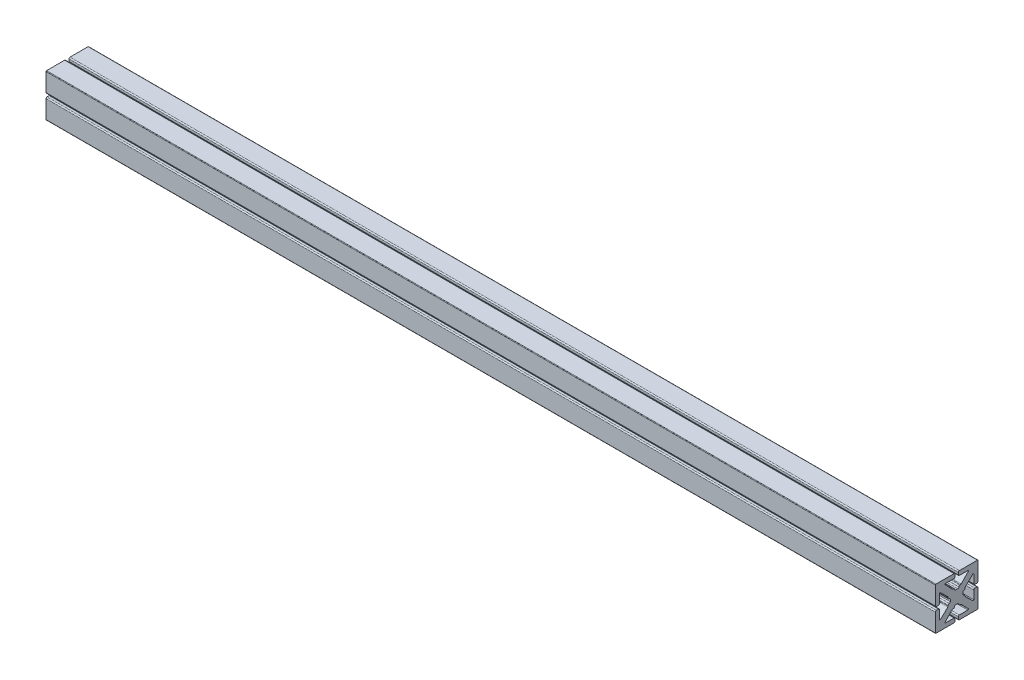
SolidWorks part; units mm, degrees
material "1060 Alloy"
ref_plane "Front Plane" through (0, 0, 0) normal (0, 0, 1) x (1, 0, 0)
ref_plane "Top Plane" through (0, 0, 0) normal (0, 1, 0) x (1, 0, 0)
ref_plane "Right Plane" through (0, 0, 0) normal (1, 0, 0) x (0, 0, -1)
sketch "Sketch1" plane through (0, 0, 0) normal (1, 0, 0) x (0, 0, -1)
  line L0 (0, 0) -> (0, 1.4986) construction
  line L1 (-0.2413, 1.4986) -> (0.2413, 1.4986)
  line L2 (5.0038, 0.635) -> (5.0038, 4.8768)
  line L3 (0.7493, 2.0066) -> (0.8825, 2.0066)
  line L4 (1.0655, 2.0845) -> (2.7141, 3.7982)
  line L5 (2.6226, 4.0132) -> (0.635, 4.0132)
  line L6 (0.381, 4.2672) -> (0.381, 4.7498)
  line L7 (0.635, 5.0038) -> (4.8768, 5.0038)
  line L8 (5.0038, 5.0038) -> (0, 0) construction
  line L9 (0, 0) -> (8.6271, 0) construction
  line L10 (0, 0) -> (0, 5.0038) construction
  line L11 (4.2672, 0.381) -> (4.7498, 0.381)
  line L12 (4.0132, 2.6226) -> (4.0132, 0.635)
  line L13 (2.0845, 1.0655) -> (3.7982, 2.7141)
  line L14 (2.0066, 0.7493) -> (2.0066, 0.8825)
  line L15 (1.4986, -0.2413) -> (1.4986, 0.2413)
  line L16 (0, 0) -> (1.4986, 0) construction
  line L17 (-0.2413, -1.4986) -> (0.2413, -1.4986)
  line L18 (0.7493, -2.0066) -> (0.8825, -2.0066)
  line L19 (1.0655, -2.0845) -> (2.7141, -3.7982)
  line L20 (2.6226, -4.0132) -> (0.635, -4.0132)
  line L21 (0.381, -4.2672) -> (0.381, -4.7498)
  line L22 (0.635, -5.0038) -> (4.8768, -5.0038)
  line L23 (5.0038, -0.635) -> (5.0038, -4.8768)
  line L24 (4.2672, -0.381) -> (4.7498, -0.381)
  line L25 (4.0132, -2.6226) -> (4.0132, -0.635)
  line L26 (2.0845, -1.0655) -> (3.7982, -2.7141)
  line L27 (2.0066, -0.7493) -> (2.0066, -0.8825)
  line L28 (-0.7493, 2.0066) -> (-0.8825, 2.0066)
  line L29 (-1.0655, 2.0845) -> (-2.7141, 3.7982)
  line L30 (-2.6226, 4.0132) -> (-0.635, 4.0132)
  line L31 (-0.381, 4.2672) -> (-0.381, 4.7498)
  line L32 (-0.635, 5.0038) -> (-4.8768, 5.0038)
  line L33 (-5.0038, 0.635) -> (-5.0038, 4.8768)
  line L34 (-4.2672, 0.381) -> (-4.7498, 0.381)
  line L35 (-4.0132, 2.6226) -> (-4.0132, 0.635)
  line L36 (-2.0845, 1.0655) -> (-3.7982, 2.7141)
  line L37 (-2.0066, 0.7493) -> (-2.0066, 0.8825)
  line L38 (-1.4986, -0.2413) -> (-1.4986, 0.2413)
  line L39 (-2.0066, -0.7493) -> (-2.0066, -0.8825)
  line L40 (-2.0845, -1.0655) -> (-3.7982, -2.7141)
  line L41 (-4.0132, -2.6226) -> (-4.0132, -0.635)
  line L42 (-4.2672, -0.381) -> (-4.7498, -0.381)
  line L43 (-5.0038, -0.635) -> (-5.0038, -4.8768)
  line L44 (-0.635, -5.0038) -> (-4.8768, -5.0038)
  line L45 (-0.381, -4.2672) -> (-0.381, -4.7498)
  line L46 (-2.6226, -4.0132) -> (-0.635, -4.0132)
  line L47 (-1.0655, -2.0845) -> (-2.7141, -3.7982)
  line L48 (-0.7493, -2.0066) -> (-0.8825, -2.0066)
  arc A0 (2.7141, 3.7982) -> (2.6226, 4.0132) centre (2.6226, 3.8862) ccw
  arc A1 (0.4953, 1.7526) -> (0.7493, 2.0066) centre (0.7493, 1.7526) cw
  arc A2 (0.8825, 2.0066) -> (1.0655, 2.0845) centre (0.8825, 2.2606) ccw
  arc A3 (0.635, 4.0132) -> (0.381, 4.2672) centre (0.635, 4.2672) cw
  arc A4 (0.381, 4.7498) -> (0.635, 5.0038) centre (0.635, 4.7498) cw
  arc A5 (0.2413, 1.4986) -> (0.4953, 1.7526) centre (0.2413, 1.7526) ccw
  arc A6 (4.7498, 0.381) -> (5.0038, 0.635) centre (4.7498, 0.635) ccw
  arc A7 (4.0132, 0.635) -> (4.2672, 0.381) centre (4.2672, 0.635) ccw
  arc A8 (3.7982, 2.7141) -> (4.0132, 2.6226) centre (3.8862, 2.6226) cw
  arc A9 (2.0066, 0.8825) -> (2.0845, 1.0655) centre (2.2606, 0.8825) cw
  arc A10 (1.7526, 0.4953) -> (2.0066, 0.7493) centre (1.7526, 0.7493) ccw
  arc A11 (1.4986, 0.2413) -> (1.7526, 0.4953) centre (1.7526, 0.2413) cw
  arc A12 (0.2413, -1.4986) -> (0.4953, -1.7526) centre (0.2413, -1.7526) cw
  arc A13 (0.4953, -1.7526) -> (0.7493, -2.0066) centre (0.7493, -1.7526) ccw
  arc A14 (0.8825, -2.0066) -> (1.0655, -2.0845) centre (0.8825, -2.2606) cw
  arc A15 (2.7141, -3.7982) -> (2.6226, -4.0132) centre (2.6226, -3.8862) cw
  arc A16 (0.635, -4.0132) -> (0.381, -4.2672) centre (0.635, -4.2672) ccw
  arc A17 (0.381, -4.7498) -> (0.635, -5.0038) centre (0.635, -4.7498) ccw
  arc A18 (4.7498, -0.381) -> (5.0038, -0.635) centre (4.7498, -0.635) cw
  arc A19 (4.0132, -0.635) -> (4.2672, -0.381) centre (4.2672, -0.635) cw
  arc A20 (3.7982, -2.7141) -> (4.0132, -2.6226) centre (3.8862, -2.6226) ccw
  arc A21 (2.0066, -0.8825) -> (2.0845, -1.0655) centre (2.2606, -0.8825) ccw
  arc A22 (1.7526, -0.4953) -> (2.0066, -0.7493) centre (1.7526, -0.7493) cw
  arc A23 (1.4986, -0.2413) -> (1.7526, -0.4953) centre (1.7526, -0.2413) ccw
  arc A24 (-0.2413, 1.4986) -> (-0.4953, 1.7526) centre (-0.2413, 1.7526) cw
  arc A25 (-0.4953, 1.7526) -> (-0.7493, 2.0066) centre (-0.7493, 1.7526) ccw
  arc A26 (-0.8825, 2.0066) -> (-1.0655, 2.0845) centre (-0.8825, 2.2606) cw
  arc A27 (-2.7141, 3.7982) -> (-2.6226, 4.0132) centre (-2.6226, 3.8862) cw
  arc A28 (-0.635, 4.0132) -> (-0.381, 4.2672) centre (-0.635, 4.2672) ccw
  arc A29 (-0.381, 4.7498) -> (-0.635, 5.0038) centre (-0.635, 4.7498) ccw
  arc A30 (-4.7498, 0.381) -> (-5.0038, 0.635) centre (-4.7498, 0.635) cw
  arc A31 (-4.0132, 0.635) -> (-4.2672, 0.381) centre (-4.2672, 0.635) cw
  arc A32 (-3.7982, 2.7141) -> (-4.0132, 2.6226) centre (-3.8862, 2.6226) ccw
  arc A33 (-2.0066, 0.8825) -> (-2.0845, 1.0655) centre (-2.2606, 0.8825) ccw
  arc A34 (-1.7526, 0.4953) -> (-2.0066, 0.7493) centre (-1.7526, 0.7493) cw
  arc A35 (-1.4986, 0.2413) -> (-1.7526, 0.4953) centre (-1.7526, 0.2413) ccw
  arc A36 (-1.4986, -0.2413) -> (-1.7526, -0.4953) centre (-1.7526, -0.2413) cw
  arc A37 (-1.7526, -0.4953) -> (-2.0066, -0.7493) centre (-1.7526, -0.7493) ccw
  arc A38 (-2.0066, -0.8825) -> (-2.0845, -1.0655) centre (-2.2606, -0.8825) cw
  arc A39 (-3.7982, -2.7141) -> (-4.0132, -2.6226) centre (-3.8862, -2.6226) cw
  arc A40 (-4.0132, -0.635) -> (-4.2672, -0.381) centre (-4.2672, -0.635) ccw
  arc A41 (-4.7498, -0.381) -> (-5.0038, -0.635) centre (-4.7498, -0.635) ccw
  arc A42 (-0.381, -4.7498) -> (-0.635, -5.0038) centre (-0.635, -4.7498) cw
  arc A43 (-0.635, -4.0132) -> (-0.381, -4.2672) centre (-0.635, -4.2672) cw
  arc A44 (-2.7141, -3.7982) -> (-2.6226, -4.0132) centre (-2.6226, -3.8862) ccw
  arc A45 (-0.8825, -2.0066) -> (-1.0655, -2.0845) centre (-0.8825, -2.2606) ccw
  arc A46 (-0.4953, -1.7526) -> (-0.7493, -2.0066) centre (-0.7493, -1.7526) cw
  arc A47 (-0.2413, -1.4986) -> (-0.4953, -1.7526) centre (-0.2413, -1.7526) ccw
  arc A48 (-4.8768, 5.0038) -> (-5.0038, 4.8768) centre (-4.8768, 4.8768) ccw
  arc A49 (-5.0038, -4.8768) -> (-4.8768, -5.0038) centre (-4.8768, -4.8768) ccw
  arc A50 (4.8768, -5.0038) -> (5.0038, -4.8768) centre (4.8768, -4.8768) ccw
  arc A51 (4.8768, 5.0038) -> (5.0038, 4.8768) centre (4.8768, 4.8768) cw
  point P14 (2.921, 4.0132)
  point P19 (0.9906, 2.0066)
  point P150 (0, -1.4986)
  point P152 (-5.0038, 5.0038)
  point P155 (-5.0038, -5.0038)
  point P158 (5.0038, -5.0038)
  dimension "D10" = 0.127
  dimension "D11" = 0.254
  dimension "D2" = 0.127
  dimension "D1" = 10.0076
  dimension "D3" = 2.9972
  dimension "D4" = 0.508
  dimension "D5" = 0.762
  dimension "D6" = 0.9906
  dimension "D7" = 2.54
  dimension "D8" = 1.9812
  dimension "D9" = 0.9906
extrude "Boss-Extrude1" add sketch "Sketch1" along normal blind 2.54 contours L33 A48 L32 A29 L31 A28 L30 A27 L29 A26 L28 A25 A24 L1 A5 A1 L3 A2 L4 A0 L5 A3 L6 A4 L7 A51 L2 A6 L11 A7 L12 A8 L13 A9 L14 A10 A11 L15 A23 A22 L27 A21 L26 A20 L25 A19 L24 A18 L23 A50 L22 A17 L21 A16 L20 A15 L19 A14 L18 A13 A12 L17 A47 A46 L48 A45 L47 A44 L46 A43 L45 A42 L44 A49 L43 A41 L42 A40 L41 A39 L40 A38 L39 A37 A36 L38 A35 A34 L37 A33 L36 A32 L35 A31 L34 A30
scale "Scale1" scale about centroid uniform scaling yes scale factor 8
sketch "Sketch2" plane through (0, 0, 0) normal (1, 0, 0) x (0, 0, -1)
  line L44 (-37.9984, 3.048) -> (-34.1376, 3.048)
  line L45 (-32.1056, 5.08) -> (-32.1056, 20.9808)
  line L46 (-30.3852, 21.7129) -> (-16.676, 8.5244)
  line L47 (-16.0528, 7.06) -> (-16.0528, 5.9944)
  line L48 (-11.9888, 1.9304) -> (-11.9888, -1.9304)
  line L49 (-16.0528, -5.9944) -> (-16.0528, -7.06)
  line L50 (-16.676, -8.5244) -> (-30.3852, -21.7129)
  line L51 (-32.1056, -20.9808) -> (-32.1056, -5.08)
  line L52 (-34.1376, -3.048) -> (-37.9984, -3.048)
  line L53 (-40.0304, -5.08) -> (-40.0304, -39.0144)
  line L54 (-39.0144, -40.0304) -> (-5.08, -40.0304)
  line L55 (-3.048, -37.9984) -> (-3.048, -34.1376)
  line L56 (-5.08, -32.1056) -> (-20.9808, -32.1056)
  line L57 (-21.7129, -30.3852) -> (-8.5244, -16.676)
  line L58 (-7.06, -16.0528) -> (-5.9944, -16.0528)
  line L59 (-1.9304, -11.9888) -> (1.9304, -11.9888)
  line L60 (5.9944, -16.0528) -> (7.06, -16.0528)
  line L61 (8.5244, -16.676) -> (21.7129, -30.3852)
  line L62 (20.9808, -32.1056) -> (5.08, -32.1056)
  line L63 (3.048, -34.1376) -> (3.048, -37.9984)
  line L64 (5.08, -40.0304) -> (39.0144, -40.0304)
  line L65 (40.0304, -39.0144) -> (40.0304, -5.08)
  line L66 (37.9984, -3.048) -> (34.1376, -3.048)
  line L67 (32.1056, -5.08) -> (32.1056, -20.9808)
  line L68 (30.3852, -21.7129) -> (16.676, -8.5244)
  line L69 (16.0528, -7.06) -> (16.0528, -5.9944)
  line L70 (11.9888, -1.9304) -> (11.9888, 1.9304)
  line L71 (16.0528, 5.9944) -> (16.0528, 7.06)
  line L72 (16.676, 8.5244) -> (30.3852, 21.7129)
  line L73 (32.1056, 20.9808) -> (32.1056, 5.08)
  line L74 (34.1376, 3.048) -> (37.9984, 3.048)
  line L75 (40.0304, 5.08) -> (40.0304, 39.0144)
  line L76 (39.0144, 40.0304) -> (5.08, 40.0304)
  line L77 (3.048, 37.9984) -> (3.048, 34.1376)
  line L78 (5.08, 32.1056) -> (20.9808, 32.1056)
  line L79 (21.7129, 30.3852) -> (8.5244, 16.676)
  line L80 (7.06, 16.0528) -> (5.9944, 16.0528)
  line L81 (1.9304, 11.9888) -> (-1.9304, 11.9888)
  line L82 (-5.9944, 16.0528) -> (-7.06, 16.0528)
  line L83 (-8.5244, 16.676) -> (-21.7129, 30.3852)
  line L84 (-20.9808, 32.1056) -> (-5.08, 32.1056)
  line L85 (-3.048, 34.1376) -> (-3.048, 37.9984)
  line L86 (-5.08, 40.0304) -> (-39.0144, 40.0304)
  line L87 (-40.0304, 39.0144) -> (-40.0304, 5.08)
  line L88 (-37.9984, 3.048) -> (-34.1376, 3.048)
  line L89 (-32.1056, 5.08) -> (-32.1056, 20.9808)
  line L90 (-30.3852, 21.7129) -> (-16.676, 8.5244)
  line L91 (-16.0528, 7.06) -> (-16.0528, 5.9944)
  line L92 (-11.9888, 1.9304) -> (-11.9888, -1.9304)
  line L93 (-16.0528, -5.9944) -> (-16.0528, -7.06)
  line L94 (-16.676, -8.5244) -> (-30.3852, -21.7129)
  line L95 (-32.1056, -20.9808) -> (-32.1056, -5.08)
  line L96 (-34.1376, -3.048) -> (-37.9984, -3.048)
  line L97 (-40.0304, -5.08) -> (-40.0304, -39.0144)
  line L98 (-39.0144, -40.0304) -> (-5.08, -40.0304)
  line L99 (-3.048, -37.9984) -> (-3.048, -34.1376)
  line L100 (-5.08, -32.1056) -> (-20.9808, -32.1056)
  line L101 (-21.7129, -30.3852) -> (-8.5244, -16.676)
  line L102 (-7.06, -16.0528) -> (-5.9944, -16.0528)
  line L103 (-1.9304, -11.9888) -> (1.9304, -11.9888)
  line L104 (5.9944, -16.0528) -> (7.06, -16.0528)
  line L105 (8.5244, -16.676) -> (21.7129, -30.3852)
  line L106 (20.9808, -32.1056) -> (5.08, -32.1056)
  line L107 (3.048, -34.1376) -> (3.048, -37.9984)
  line L108 (5.08, -40.0304) -> (39.0144, -40.0304)
  line L109 (40.0304, -39.0144) -> (40.0304, -5.08)
  line L110 (37.9984, -3.048) -> (34.1376, -3.048)
  line L111 (32.1056, -5.08) -> (32.1056, -20.9808)
  line L112 (30.3852, -21.7129) -> (16.676, -8.5244)
  line L113 (16.0528, -7.06) -> (16.0528, -5.9944)
  line L114 (11.9888, -1.9304) -> (11.9888, 1.9304)
  line L115 (16.0528, 5.9944) -> (16.0528, 7.06)
  line L116 (16.676, 8.5244) -> (30.3852, 21.7129)
  line L117 (32.1056, 20.9808) -> (32.1056, 5.08)
  line L118 (34.1376, 3.048) -> (37.9984, 3.048)
  line L119 (40.0304, 5.08) -> (40.0304, 39.0144)
  line L120 (39.0144, 40.0304) -> (5.08, 40.0304)
  line L121 (3.048, 37.9984) -> (3.048, 34.1376)
  line L122 (5.08, 32.1056) -> (20.9808, 32.1056)
  line L123 (21.7129, 30.3852) -> (8.5244, 16.676)
  line L124 (7.06, 16.0528) -> (5.9944, 16.0528)
  line L125 (1.9304, 11.9888) -> (-1.9304, 11.9888)
  line L126 (-5.9944, 16.0528) -> (-7.06, 16.0528)
  line L127 (-8.5244, 16.676) -> (-21.7129, 30.3852)
  line L128 (-20.9808, 32.1056) -> (-5.08, 32.1056)
  line L129 (-3.048, 34.1376) -> (-3.048, 37.9984)
  line L130 (-5.08, 40.0304) -> (-39.0144, 40.0304)
  line L131 (-40.0304, 39.0144) -> (-40.0304, 5.08)
  arc A52 (-40.0304, 5.08) -> (-37.9984, 3.048) centre (-37.9984, 5.08) ccw
  arc A53 (-34.1376, 3.048) -> (-32.1056, 5.08) centre (-34.1376, 5.08) ccw
  arc A54 (-30.3852, 21.7129) -> (-32.1056, 20.9808) centre (-31.0896, 20.9808) ccw
  arc A55 (-16.0528, 7.06) -> (-16.676, 8.5244) centre (-18.0848, 7.06) ccw
  arc A56 (-16.0528, 5.9944) -> (-14.0208, 3.9624) centre (-14.0208, 5.9944) ccw
  arc A57 (-11.9888, 1.9304) -> (-14.0208, 3.9624) centre (-14.0208, 1.9304) ccw
  arc A58 (-14.0208, -3.9624) -> (-11.9888, -1.9304) centre (-14.0208, -1.9304) ccw
  arc A59 (-14.0208, -3.9624) -> (-16.0528, -5.9944) centre (-14.0208, -5.9944) ccw
  arc A60 (-16.676, -8.5244) -> (-16.0528, -7.06) centre (-18.0848, -7.06) ccw
  arc A61 (-32.1056, -20.9808) -> (-30.3852, -21.7129) centre (-31.0896, -20.9808) ccw
  arc A62 (-32.1056, -5.08) -> (-34.1376, -3.048) centre (-34.1376, -5.08) ccw
  arc A63 (-37.9984, -3.048) -> (-40.0304, -5.08) centre (-37.9984, -5.08) ccw
  arc A64 (-40.0304, -39.0144) -> (-39.0144, -40.0304) centre (-39.0144, -39.0144) ccw
  arc A65 (-5.08, -40.0304) -> (-3.048, -37.9984) centre (-5.08, -37.9984) ccw
  arc A66 (-3.048, -34.1376) -> (-5.08, -32.1056) centre (-5.08, -34.1376) ccw
  arc A67 (-21.7129, -30.3852) -> (-20.9808, -32.1056) centre (-20.9808, -31.0896) ccw
  arc A68 (-7.06, -16.0528) -> (-8.5244, -16.676) centre (-7.06, -18.0848) ccw
  arc A69 (-5.9944, -16.0528) -> (-3.9624, -14.0208) centre (-5.9944, -14.0208) ccw
  arc A70 (-1.9304, -11.9888) -> (-3.9624, -14.0208) centre (-1.9304, -14.0208) ccw
  arc A71 (3.9624, -14.0208) -> (1.9304, -11.9888) centre (1.9304, -14.0208) ccw
  arc A72 (3.9624, -14.0208) -> (5.9944, -16.0528) centre (5.9944, -14.0208) ccw
  arc A73 (8.5244, -16.676) -> (7.06, -16.0528) centre (7.06, -18.0848) ccw
  arc A74 (20.9808, -32.1056) -> (21.7129, -30.3852) centre (20.9808, -31.0896) ccw
  arc A75 (5.08, -32.1056) -> (3.048, -34.1376) centre (5.08, -34.1376) ccw
  arc A76 (3.048, -37.9984) -> (5.08, -40.0304) centre (5.08, -37.9984) ccw
  arc A77 (39.0144, -40.0304) -> (40.0304, -39.0144) centre (39.0144, -39.0144) ccw
  arc A78 (40.0304, -5.08) -> (37.9984, -3.048) centre (37.9984, -5.08) ccw
  arc A79 (34.1376, -3.048) -> (32.1056, -5.08) centre (34.1376, -5.08) ccw
  arc A80 (30.3852, -21.7129) -> (32.1056, -20.9808) centre (31.0896, -20.9808) ccw
  arc A81 (16.0528, -7.06) -> (16.676, -8.5244) centre (18.0848, -7.06) ccw
  arc A82 (16.0528, -5.9944) -> (14.0208, -3.9624) centre (14.0208, -5.9944) ccw
  arc A83 (11.9888, -1.9304) -> (14.0208, -3.9624) centre (14.0208, -1.9304) ccw
  arc A84 (14.0208, 3.9624) -> (11.9888, 1.9304) centre (14.0208, 1.9304) ccw
  arc A85 (14.0208, 3.9624) -> (16.0528, 5.9944) centre (14.0208, 5.9944) ccw
  arc A86 (16.676, 8.5244) -> (16.0528, 7.06) centre (18.0848, 7.06) ccw
  arc A87 (32.1056, 20.9808) -> (30.3852, 21.7129) centre (31.0896, 20.9808) ccw
  arc A88 (32.1056, 5.08) -> (34.1376, 3.048) centre (34.1376, 5.08) ccw
  arc A89 (37.9984, 3.048) -> (40.0304, 5.08) centre (37.9984, 5.08) ccw
  arc A90 (40.0304, 39.0144) -> (39.0144, 40.0304) centre (39.0144, 39.0144) ccw
  arc A91 (5.08, 40.0304) -> (3.048, 37.9984) centre (5.08, 37.9984) ccw
  arc A92 (3.048, 34.1376) -> (5.08, 32.1056) centre (5.08, 34.1376) ccw
  arc A93 (21.7129, 30.3852) -> (20.9808, 32.1056) centre (20.9808, 31.0896) ccw
  arc A94 (7.06, 16.0528) -> (8.5244, 16.676) centre (7.06, 18.0848) ccw
  arc A95 (5.9944, 16.0528) -> (3.9624, 14.0208) centre (5.9944, 14.0208) ccw
  arc A96 (1.9304, 11.9888) -> (3.9624, 14.0208) centre (1.9304, 14.0208) ccw
  arc A97 (-3.9624, 14.0208) -> (-1.9304, 11.9888) centre (-1.9304, 14.0208) ccw
  arc A98 (-3.9624, 14.0208) -> (-5.9944, 16.0528) centre (-5.9944, 14.0208) ccw
  arc A99 (-8.5244, 16.676) -> (-7.06, 16.0528) centre (-7.06, 18.0848) ccw
  arc A100 (-20.9808, 32.1056) -> (-21.7129, 30.3852) centre (-20.9808, 31.0896) ccw
  arc A101 (-5.08, 32.1056) -> (-3.048, 34.1376) centre (-5.08, 34.1376) ccw
  arc A102 (-3.048, 37.9984) -> (-5.08, 40.0304) centre (-5.08, 37.9984) ccw
  arc A103 (-39.0144, 40.0304) -> (-40.0304, 39.0144) centre (-39.0144, 39.0144) ccw
  arc A104 (-40.0304, 5.08) -> (-37.9984, 3.048) centre (-37.9984, 5.08) ccw
  arc A105 (-34.1376, 3.048) -> (-32.1056, 5.08) centre (-34.1376, 5.08) ccw
  arc A106 (-30.3852, 21.7129) -> (-32.1056, 20.9808) centre (-31.0896, 20.9808) ccw
  arc A107 (-16.0528, 7.06) -> (-16.676, 8.5244) centre (-18.0848, 7.06) ccw
  arc A108 (-16.0528, 5.9944) -> (-14.0208, 3.9624) centre (-14.0208, 5.9944) ccw
  arc A109 (-11.9888, 1.9304) -> (-14.0208, 3.9624) centre (-14.0208, 1.9304) ccw
  arc A110 (-14.0208, -3.9624) -> (-11.9888, -1.9304) centre (-14.0208, -1.9304) ccw
  arc A111 (-14.0208, -3.9624) -> (-16.0528, -5.9944) centre (-14.0208, -5.9944) ccw
  arc A112 (-16.676, -8.5244) -> (-16.0528, -7.06) centre (-18.0848, -7.06) ccw
  arc A113 (-32.1056, -20.9808) -> (-30.3852, -21.7129) centre (-31.0896, -20.9808) ccw
  arc A114 (-32.1056, -5.08) -> (-34.1376, -3.048) centre (-34.1376, -5.08) ccw
  arc A115 (-37.9984, -3.048) -> (-40.0304, -5.08) centre (-37.9984, -5.08) ccw
  arc A116 (-40.0304, -39.0144) -> (-39.0144, -40.0304) centre (-39.0144, -39.0144) ccw
  arc A117 (-5.08, -40.0304) -> (-3.048, -37.9984) centre (-5.08, -37.9984) ccw
  arc A118 (-3.048, -34.1376) -> (-5.08, -32.1056) centre (-5.08, -34.1376) ccw
  arc A119 (-21.7129, -30.3852) -> (-20.9808, -32.1056) centre (-20.9808, -31.0896) ccw
  arc A120 (-7.06, -16.0528) -> (-8.5244, -16.676) centre (-7.06, -18.0848) ccw
  arc A121 (-5.9944, -16.0528) -> (-3.9624, -14.0208) centre (-5.9944, -14.0208) ccw
  arc A122 (-1.9304, -11.9888) -> (-3.9624, -14.0208) centre (-1.9304, -14.0208) ccw
  arc A123 (3.9624, -14.0208) -> (1.9304, -11.9888) centre (1.9304, -14.0208) ccw
  arc A124 (3.9624, -14.0208) -> (5.9944, -16.0528) centre (5.9944, -14.0208) ccw
  arc A125 (8.5244, -16.676) -> (7.06, -16.0528) centre (7.06, -18.0848) ccw
  arc A126 (20.9808, -32.1056) -> (21.7129, -30.3852) centre (20.9808, -31.0896) ccw
  arc A127 (5.08, -32.1056) -> (3.048, -34.1376) centre (5.08, -34.1376) ccw
  arc A128 (3.048, -37.9984) -> (5.08, -40.0304) centre (5.08, -37.9984) ccw
  arc A129 (39.0144, -40.0304) -> (40.0304, -39.0144) centre (39.0144, -39.0144) ccw
  arc A130 (40.0304, -5.08) -> (37.9984, -3.048) centre (37.9984, -5.08) ccw
  arc A131 (34.1376, -3.048) -> (32.1056, -5.08) centre (34.1376, -5.08) ccw
  arc A132 (30.3852, -21.7129) -> (32.1056, -20.9808) centre (31.0896, -20.9808) ccw
  arc A133 (16.0528, -7.06) -> (16.676, -8.5244) centre (18.0848, -7.06) ccw
  arc A134 (16.0528, -5.9944) -> (14.0208, -3.9624) centre (14.0208, -5.9944) ccw
  arc A135 (11.9888, -1.9304) -> (14.0208, -3.9624) centre (14.0208, -1.9304) ccw
  arc A136 (14.0208, 3.9624) -> (11.9888, 1.9304) centre (14.0208, 1.9304) ccw
  arc A137 (14.0208, 3.9624) -> (16.0528, 5.9944) centre (14.0208, 5.9944) ccw
  arc A138 (16.676, 8.5244) -> (16.0528, 7.06) centre (18.0848, 7.06) ccw
  arc A139 (32.1056, 20.9808) -> (30.3852, 21.7129) centre (31.0896, 20.9808) ccw
  arc A140 (32.1056, 5.08) -> (34.1376, 3.048) centre (34.1376, 5.08) ccw
  arc A141 (37.9984, 3.048) -> (40.0304, 5.08) centre (37.9984, 5.08) ccw
  arc A142 (40.0304, 39.0144) -> (39.0144, 40.0304) centre (39.0144, 39.0144) ccw
  arc A143 (5.08, 40.0304) -> (3.048, 37.9984) centre (5.08, 37.9984) ccw
  arc A144 (3.048, 34.1376) -> (5.08, 32.1056) centre (5.08, 34.1376) ccw
  arc A145 (21.7129, 30.3852) -> (20.9808, 32.1056) centre (20.9808, 31.0896) ccw
  arc A146 (7.06, 16.0528) -> (8.5244, 16.676) centre (7.06, 18.0848) ccw
  arc A147 (5.9944, 16.0528) -> (3.9624, 14.0208) centre (5.9944, 14.0208) ccw
  arc A148 (1.9304, 11.9888) -> (3.9624, 14.0208) centre (1.9304, 14.0208) ccw
  arc A149 (-3.9624, 14.0208) -> (-1.9304, 11.9888) centre (-1.9304, 14.0208) ccw
  arc A150 (-3.9624, 14.0208) -> (-5.9944, 16.0528) centre (-5.9944, 14.0208) ccw
  arc A151 (-8.5244, 16.676) -> (-7.06, 16.0528) centre (-7.06, 18.0848) ccw
  arc A152 (-20.9808, 32.1056) -> (-21.7129, 30.3852) centre (-20.9808, 31.0896) ccw
  arc A153 (-5.08, 32.1056) -> (-3.048, 34.1376) centre (-5.08, 34.1376) ccw
  arc A154 (-3.048, 37.9984) -> (-5.08, 40.0304) centre (-5.08, 37.9984) ccw
  arc A155 (-39.0144, 40.0304) -> (-40.0304, 39.0144) centre (-39.0144, 39.0144) ccw
  dimension "D1" = 0
extrude "Boss-Extrude2" add sketch "Sketch2" along normal mid plane 1670
ref_point "Point1"
ref_point "Point2"
